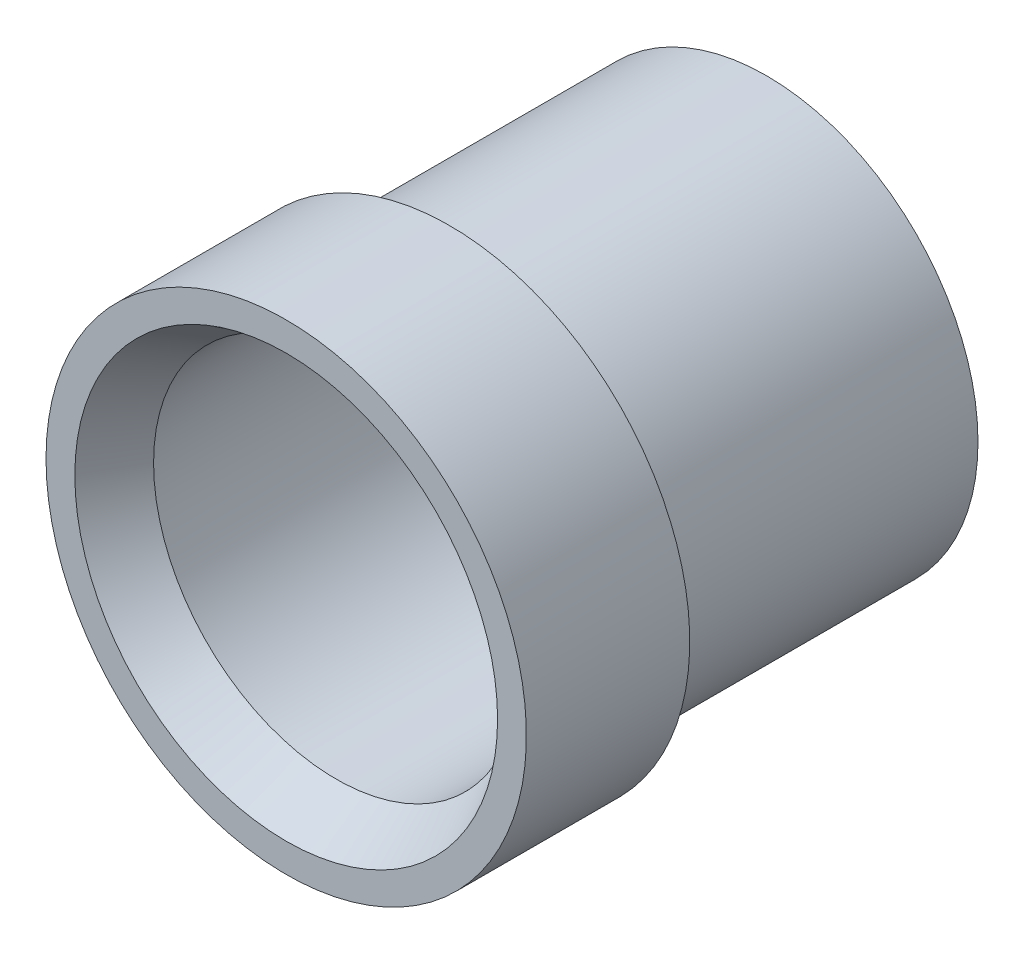
SolidWorks part; units mm, degrees
ref_plane "Front" through (0, 0, 0) normal (0, 0, 1) x (1, 0, 0)
ref_plane "Top" through (0, 0, 0) normal (0, 1, 0) x (1, 0, 0)
ref_plane "Right" through (0, 0, 0) normal (1, 0, 0) x (0, 0, -1)
sketch "Sketch1" plane through (0, 0, 0) normal (1, 0, 0) x (0, 0, -1)
  line L0 (-6.35, 5.588) -> (-5.0302, 4.826)
  line L1 (6.35, 4.826) -> (6.35, 5.588)
  line L2 (6.35, 5.588) -> (-2.032, 5.588)
  line L3 (-2.032, 5.588) -> (-2.032, 6.35)
  line L4 (-2.032, 6.35) -> (-6.35, 6.35)
  line L5 (-6.35, 6.35) -> (-6.35, 5.588)
  line L6 (-5.0302, 4.826) -> (6.35, 4.826)
  line L7 (6.35, 0) -> (-6.35, 0) construction
  dimension "D1" = 30
  dimension "Length" = 12.7
  dimension "Band" = 4.318
  dimension "Max OD" = 12.7
  dimension "ID" = 9.652
revolve "Revolve1" add sketch "Sketch1" angle 360 about L7
